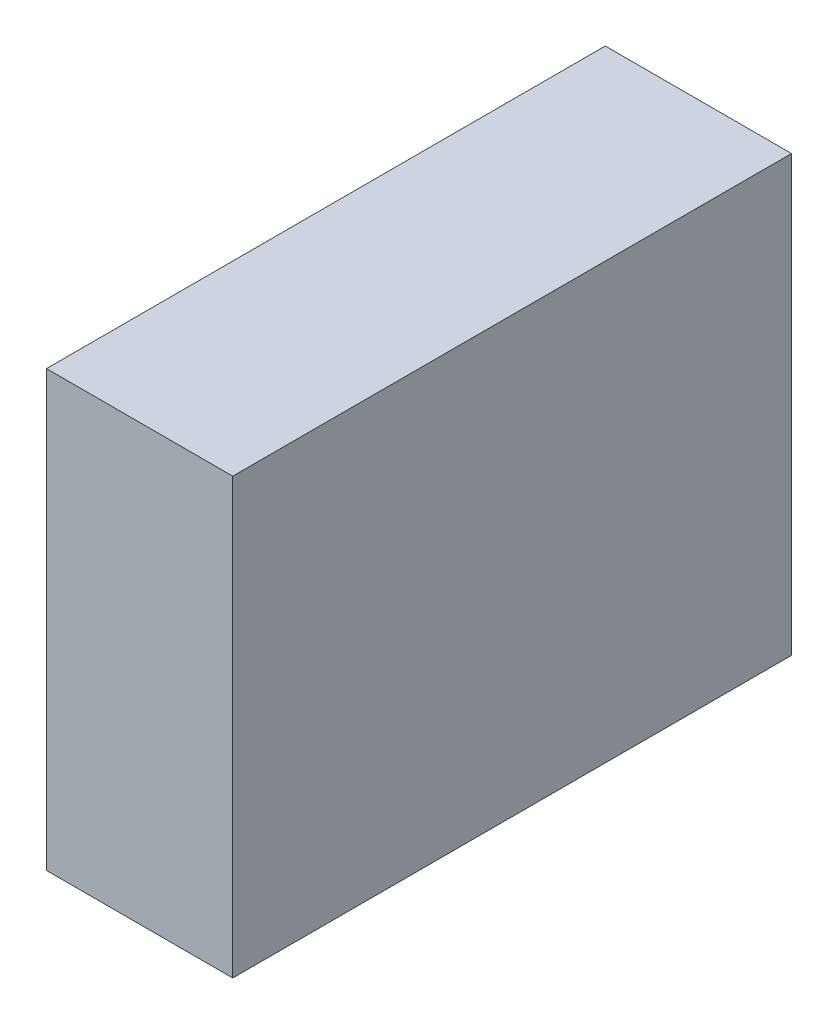
SolidWorks part; units mm, degrees
ref_plane "Front Plane" through (0, 0, 0) normal (0, 0, 1) x (1, 0, 0)
ref_plane "Top Plane" through (0, 0, 0) normal (0, 1, 0) x (1, 0, 0)
ref_plane "Right Plane" through (0, 0, 0) normal (1, 0, 0) x (0, 0, -1)
sketch "Sketch1" plane through (0, 0, 0) normal (0, 0, 1) x (1, 0, 0)
  line L0 (920, 490) -> (920, 560)
  line L1 (920, 560) -> (950, 560)
  line L2 (950, 560) -> (950, 490)
  line L3 (950, 490) -> (920, 490)
extrude "Boss-Extrude1" add sketch "Sketch1" along normal blind 90
